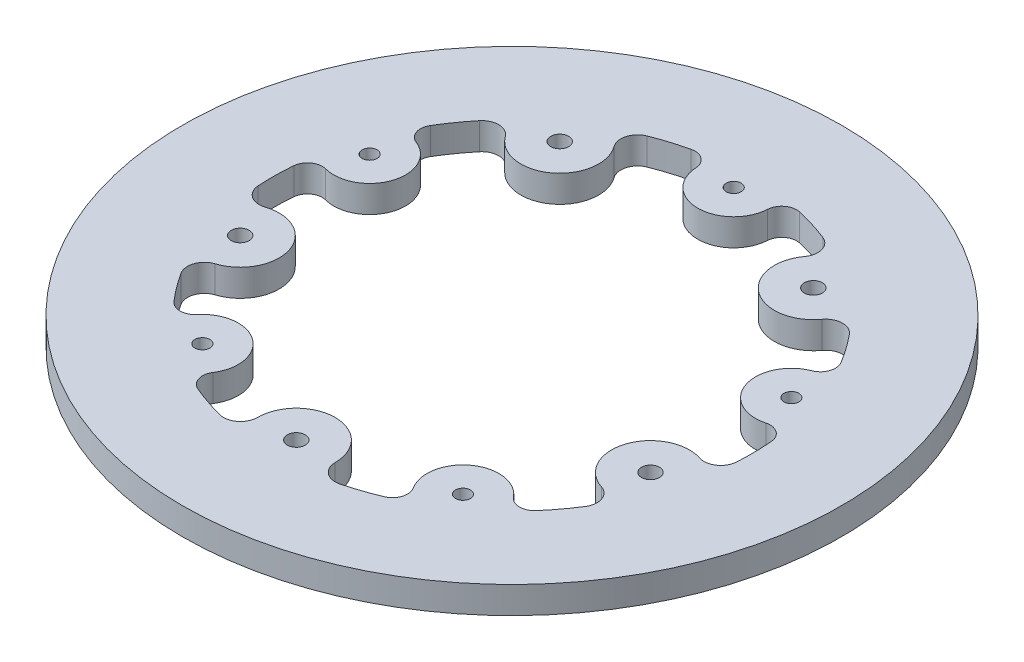
SolidWorks part; units mm, degrees
ref_plane "Front" through (0, 0, 0) normal (0, 0, 1) x (1, 0, 0)
ref_plane "Top" through (0, 0, 0) normal (0, 1, 0) x (1, 0, 0)
ref_plane "Right" through (0, 0, 0) normal (1, 0, 0) x (0, 0, -1)
sketch "Sketch2" plane through (0, 0, 0) normal (0, 1, 0) x (1, 0, 0)
  line L0 (0, 0) -> (0, 110) construction
  line L1 (0, 0) -> (104.6162, 33.9919) construction
  line L2 (0, 0) -> (64.6564, -88.9919) construction
  line L3 (0, 0) -> (-64.6564, -88.9919) construction
  line L4 (0, 0) -> (-104.6162, 33.9919) construction
  line L5 (0, 0) -> (0, -80) construction
  line L6 (-10.8095, -80) -> (10.8095, -80) construction
  line L7 (-12.6491, -75) -> (12.6491, -75) construction
  line L8 (-13, -72) -> (13, -72) construction
  line L9 (-13, -72) -> (-13, -52.7888) construction
  line L10 (0, 0) -> (-76.0845, -24.7214) construction
  line L11 (-75.238, -11.1463) -> (-67.4204, -35.2063) construction
  line L12 (-72.4933, -9.8855) -> (-64.4588, -34.613) construction
  line L14 (0, 0) -> (-47.0228, 64.7214) construction
  line L15 (-33.8505, 68.1112) -> (-54.3172, 53.2413) construction
  line L16 (-31.8033, 65.8904) -> (-52.8378, 50.608) construction
  line L17 (-47.0228, 64.7214) -> (-55.7679, 58.3677) construction
  line L18 (0, 0) -> (47.0228, 64.7214) construction
  line L19 (54.3172, 53.2413) -> (33.8505, 68.1112) construction
  line L20 (52.8378, 50.608) -> (31.8033, 65.8904) construction
  line L21 (55.7679, 58.3677) -> (38.2778, 71.075) construction
  line L22 (0, 0) -> (76.0845, -24.7214) construction
  line L23 (67.4204, -35.2063) -> (75.238, -11.1463) construction
  line L24 (64.4588, -34.613) -> (72.4933, -9.8855) construction
  line L25 (72.7442, -35.0018) -> (79.4248, -14.4409) construction
  line L26 (-79.4248, -14.4409) -> (-76.0845, -24.7214) construction
  arc A0 (-18.1052, 77.9243) -> (-29.3118, 74.4367) centre (0, 0) ccw
  circle A1 centre (0, 0) radius 110
  circle A2 centre (0, 74) radius 6 construction
  circle A3 centre (0, 74) radius 2
  arc A4 (-11.9814, 73.3323) -> (11.9814, 73.3323) centre (0, 74) ccw
  circle A5 centre (70.3782, 22.8673) radius 2
  circle A6 centre (70.3782, 22.8673) radius 6 construction
  arc A7 (66.0407, 34.0559) -> (73.4456, 11.2659) centre (70.3782, 22.8673) ccw
  circle A8 centre (43.4961, -59.8673) radius 2
  circle A9 centre (43.4961, -59.8673) radius 6 construction
  arc A10 (52.7968, -52.2846) -> (33.4105, -66.3696) centre (43.4961, -59.8673) ccw
  circle A11 centre (-43.4961, -59.8673) radius 2
  circle A12 centre (-43.4961, -59.8673) radius 6 construction
  arc A13 (-33.4105, -66.3696) -> (-52.7968, -52.2846) centre (-43.4961, -59.8673) ccw
  circle A14 centre (-70.3782, 22.8673) radius 2
  circle A15 centre (-70.3782, 22.8673) radius 6 construction
  arc A16 (-73.4456, 11.2659) -> (-66.0407, 34.0559) centre (-70.3782, 22.8673) ccw
  arc A17 (68.5156, 41.299) -> (61.7356, 50.8794) centre (0, 0) ccw
  arc A18 (60.4502, -52.4001) -> (67.4665, -42.9915) centre (0, 0) ccw
  arc A19 (-31.1553, -73.6841) -> (-20.039, -77.4496) centre (0, 0) ccw
  arc A20 (-79.7053, 6.8608) -> (-79.8513, -4.875) centre (0, 0) ccw
  circle A21 centre (0, -72) radius 3
  arc A22 (-13, -72) -> (13, -72) centre (0, -72) cw
  arc A23 (-13, -72) -> (-20.039, -77.4496) centre (-18.629, -72) cw
  arc A24 (13, -72) -> (20.039, -77.4496) centre (18.629, -72) ccw
  arc A25 (-72.4933, -9.8855) -> (-79.8513, -4.875) centre (-74.2328, -4.532) cw
  circle A26 centre (-68.4761, -22.2492) radius 3
  arc A27 (-72.4933, -9.8855) -> (-64.4588, -34.613) centre (-68.4761, -22.2492) cw
  arc A28 (-64.4588, -34.613) -> (-67.4665, -42.9915) centre (-62.7194, -39.9665) ccw
  arc A29 (-31.8033, 65.8904) -> (-29.3118, 74.4367) centre (-27.2493, 69.1991) cw
  circle A30 centre (-42.3205, 58.2492) radius 3
  arc A31 (-31.8033, 65.8904) -> (-52.8378, 50.608) centre (-42.3205, 58.2492) cw
  arc A32 (-52.8378, 50.608) -> (-61.7356, 50.8794) centre (-57.3917, 47.2994) ccw
  arc A33 (52.8378, 50.608) -> (61.7356, 50.8794) centre (57.3917, 47.2994) cw
  circle A34 centre (42.3205, 58.2492) radius 3
  arc A35 (52.8378, 50.608) -> (31.8033, 65.8904) centre (42.3205, 58.2492) cw
  arc A36 (31.8033, 65.8904) -> (29.3118, 74.4367) centre (27.2493, 69.1991) ccw
  arc A37 (64.4588, -34.613) -> (67.4665, -42.9915) centre (62.7194, -39.9665) cw
  circle A38 centre (68.4761, -22.2492) radius 3
  arc A39 (64.4588, -34.613) -> (72.4933, -9.8855) centre (68.4761, -22.2492) cw
  arc A40 (72.4933, -9.8855) -> (79.8513, -4.875) centre (74.2328, -4.532) ccw
  arc A41 (20.039, -77.4496) -> (31.1553, -73.6841) centre (0, 0) ccw
  arc A42 (-20.039, -77.4496) -> (20.039, -77.4496) centre (0, 0) ccw construction
  arc A43 (79.8513, -4.875) -> (79.7053, 6.8608) centre (0, 0) ccw
  arc A44 (29.3118, 74.4367) -> (18.1052, 77.9243) centre (0, 0) ccw
  arc A45 (-61.7356, 50.8794) -> (-68.5156, 41.299) centre (0, 0) ccw
  arc A46 (-67.4665, -42.9915) -> (-60.4502, -52.4001) centre (0, 0) ccw
  arc A47 (-66.0407, 34.0559) -> (-68.5156, 41.299) centre (-64.2334, 38.7179) cw
  arc A48 (-73.4456, 11.2659) -> (-79.7053, 6.8608) centre (-74.7237, 6.432) ccw
  arc A49 (-52.7968, -52.2846) -> (-60.4502, -52.4001) centre (-56.6721, -49.1251) cw
  arc A50 (-33.4105, -66.3696) -> (-31.1553, -73.6841) centre (-29.2081, -69.0788) ccw
  arc A51 (52.7968, -52.2846) -> (60.4502, -52.4001) centre (56.6721, -49.1251) ccw
  arc A52 (33.4105, -66.3696) -> (31.1553, -73.6841) centre (29.2081, -69.0788) cw
  arc A53 (73.4456, 11.2659) -> (79.7053, 6.8608) centre (74.7237, 6.432) cw
  arc A54 (66.0407, 34.0559) -> (68.5156, 41.299) centre (64.2334, 38.7179) ccw
  arc A55 (-11.9814, 73.3323) -> (-18.1052, 77.9243) centre (-16.9737, 73.0541) ccw
  arc A56 (11.9814, 73.3323) -> (18.1052, 77.9243) centre (16.9737, 73.0541) cw
  point P36 (0, 0)
  point P38 (0, -80)
  point P39 (0, -80)
  point P44 (0, -75)
  point P51 (0, -72)
  point P111 (0, 0)
  dimension "D1" = 160
  dimension "D2" = 30
  dimension "D3" = 12
  dimension "D4" = 4
  dimension "D5" = 6
  dimension "D6" = 5
  dimension "D7" = 6
  dimension "D9" = 10
  dimension "D11" = 5
  dimension "D8" = 5
  dimension "D10" = 5
extrude "Boss-Extrude1" add sketch "Sketch2" along normal blind 9
sketch "Sketch3" [suppressed] plane through (0, 9, 0) normal (0, 1, 0) x (1, 0, 0)
  line L0 (0, 0) -> (0, 116.2564) construction
  line L1 (4.9616, 114.4288) -> (5.0361, 116.1472) construction
  line L2 (0, 114.5364) -> (0, 115.3964) construction
  line L3 (4.9616, 114.4288) -> (4.9988, 115.288) construction
  circle A0 centre (0, 0) radius 116.2564 construction
  circle A1 centre (0, 0) radius 112.4564 construction
  circle A2 centre (0, 0) radius 114.5364 construction
  arc A3 (-2.0799, 114.5175) -> (2.0799, 114.5175) centre (0, 114.5364) ccw
  arc A4 (2.8828, 114.5001) -> (7.0387, 114.3199) centre (4.9616, 114.4288) ccw
  arc A5 (7.8401, 114.2677) -> (11.9843, 113.9077) centre (9.9138, 114.1065) ccw
  arc A6 (12.7827, 113.8208) -> (16.9074, 113.2816) centre (14.8475, 113.5699) ccw
  arc A7 (17.7012, 113.1603) -> (21.7987, 112.4428) centre (19.7532, 112.8202) ccw
  arc A8 (22.5866, 112.2872) -> (26.6492, 111.393) centre (24.6219, 111.8586) ccw
  arc A9 (27.4295, 111.2034) -> (31.4495, 110.134) centre (29.4444, 110.687) ccw
  arc A10 (32.221, 109.9108) -> (36.1909, 108.6683) centre (34.2116, 109.3076) ccw
  arc A11 (36.9519, 108.4119) -> (40.8643, 106.9985) centre (38.9145, 107.723) ccw
  arc A12 (41.6135, 106.7094) -> (45.461, 105.1279) centre (43.5444, 105.9361) ccw
  arc A13 (46.197, 104.8066) -> (49.9723, 103.0599) centre (48.0926, 103.9504) ccw
  arc A14 (50.6937, 102.707) -> (54.3898, 100.7984) centre (52.5504, 101.7695) ccw
  arc A15 (55.0952, 100.4146) -> (58.7052, 98.3477) centre (56.9096, 99.3975) ccw
  arc A16 (59.3934, 97.9337) -> (62.9104, 95.7124) centre (61.162, 96.839) ccw
  arc A17 (63.58, 95.2689) -> (66.9975, 92.8973) centre (65.2995, 94.0986) ccw
  arc A18 (67.6472, 92.4253) -> (70.9588, 89.9079) centre (69.3145, 91.1816) ccw
  arc A19 (71.5875, 89.4081) -> (74.7869, 86.7496) centre (73.1993, 88.0934) ccw
  arc A20 (75.3933, 86.2231) -> (78.4746, 83.4285) centre (76.9466, 84.8398) ccw
  arc A21 (79.0576, 82.8762) -> (82.015, 79.9508) centre (80.5496, 81.4269) ccw
  arc A22 (82.5735, 79.3738) -> (85.4013, 76.3229) centre (84.0013, 77.8612) ccw
  arc A23 (85.9344, 75.7223) -> (88.6274, 72.5518) centre (87.2953, 74.1493) ccw
  arc A24 (89.1339, 71.9286) -> (91.687, 68.6445) centre (90.4254, 70.2981) ccw
  arc A25 (92.1661, 67.9999) -> (94.5746, 64.6083) centre (93.3857, 66.315) ccw
  arc A26 (95.0252, 63.9436) -> (97.2845, 60.4508) centre (96.1707, 62.2074) ccw
  arc A27 (97.706, 59.7672) -> (99.8119, 56.1798) centre (98.7752, 57.983) ccw
  arc A28 (100.2033, 55.4786) -> (102.1518, 51.8033) centre (101.1943, 53.6498) ccw
  arc A29 (102.5125, 51.0858) -> (104.3, 47.3296) centre (103.4233, 49.2158) ccw
  arc A30 (104.6293, 46.5972) -> (106.2523, 42.767) centre (105.4582, 44.6895) ccw
  arc A31 (106.5496, 42.021) -> (108.0052, 38.1242) centre (107.2951, 40.0792) ccw
  arc A32 (108.2699, 37.366) -> (109.5553, 33.4097) centre (108.9306, 35.3937) ccw
  arc A33 (109.7869, 32.6408) -> (110.8997, 28.6326) centre (110.3615, 30.6417) ccw
  arc A34 (111.0978, 27.8543) -> (112.036, 23.8017) centre (111.5853, 25.8322) ccw
  arc A35 (112.2001, 23.0155) -> (112.9619, 18.9261) centre (112.5996, 20.9743) ccw
  arc A36 (113.0918, 18.1336) -> (113.6757, 14.0149) centre (113.4024, 16.0769) ccw
  arc A37 (113.7712, 13.2175) -> (114.1761, 9.0775) centre (113.9924, 11.1493) ccw
  arc A38 (114.2369, 8.2767) -> (114.4621, 4.123) centre (114.3684, 6.2009) ccw
  arc A39 (114.4882, 3.3203) -> (114.5333, -0.8392) centre (114.5296, 1.2408) ccw
  arc A40 (114.5246, -1.6423) -> (114.3894, -5.7999) centre (114.4759, -3.7217) ccw
  arc A41 (114.3459, -6.6018) -> (114.0308, -10.7497) centre (114.2072, -8.6771) ccw
  arc A42 (113.9526, -11.5489) -> (113.4581, -15.6792) centre (113.7241, -13.6163) ccw
  arc A43 (113.3454, -16.4744) -> (112.6724, -20.5794) centre (113.0275, -18.5299) ccw
  arc A44 (112.5253, -21.3689) -> (111.6752, -25.4409) centre (112.1187, -23.4087) ccw
  arc A45 (111.494, -26.2233) -> (110.4683, -30.2546) centre (110.9994, -28.2436) ccw
  arc A46 (110.2534, -31.0284) -> (109.054, -35.0116) centre (109.6718, -33.0255) ccw
  arc A47 (108.8058, -35.7753) -> (107.4349, -39.7028) centre (108.1382, -37.7453) ccw
  arc A48 (107.1539, -40.4551) -> (105.6142, -44.3195) centre (106.4016, -42.3943) ccw
  arc A49 (105.3009, -45.0589) -> (103.5952, -48.853) centre (104.4653, -46.9637) ccw
  arc A50 (103.2501, -49.5781) -> (101.3817, -53.2947) centre (102.3328, -51.4449) ccw
  arc A51 (101.0056, -54.0042) -> (98.9779, -57.6364) centre (100.0082, -55.8295) ccw
  arc A52 (98.5713, -58.329) -> (96.3882, -61.8699) centre (97.4959, -60.1093) ccw
  arc A53 (95.9521, -62.5442) -> (93.6176, -65.9872) centre (94.8005, -64.2763) ccw
  arc A54 (93.1527, -66.642) -> (90.6713, -69.9807) centre (91.9271, -68.3226) ccw
  arc A55 (90.1784, -70.6147) -> (87.5547, -73.8428) centre (88.8812, -72.2407) ccw
  arc A56 (87.0348, -74.4548) -> (84.2737, -77.5662) centre (85.6684, -76.0231) ccw
  arc A57 (83.7278, -78.1552) -> (80.8345, -81.144) centre (82.2947, -79.6628) ccw
  arc A58 (80.2636, -81.7088) -> (77.2436, -84.5695) centre (78.7666, -83.1529) ccw
  arc A59 (76.6487, -85.109) -> (73.5076, -87.8362) centre (75.0906, -86.4869) ccw
  arc A60 (72.89, -88.3495) -> (69.6337, -90.938) centre (71.2736, -89.6585) ccw
  arc A61 (68.9944, -91.424) -> (65.629, -93.8691) centre (67.3228, -92.6619) ccw
  arc A62 (64.9692, -94.327) -> (61.5011, -96.624) centre (63.2456, -95.4912) ccw
  arc A63 (60.8221, -97.0528) -> (57.2577, -99.1974) centre (59.0497, -98.1413) ccw
  arc A64 (56.5608, -99.5964) -> (52.9069, -101.5846) centre (54.7429, -100.6071) ccw
  arc A65 (52.1933, -101.9531) -> (48.4567, -103.7811) centre (50.3333, -102.8841) ccw
  arc A66 (47.7279, -104.1183) -> (43.9155, -105.7828) centre (45.8293, -104.9679) ccw
  arc A67 (43.1728, -106.0881) -> (39.2919, -107.5859) centre (41.2392, -106.8546) ccw
  arc A68 (38.5366, -107.8587) -> (34.5946, -109.187) centre (36.5716, -108.5407) ccw
  arc A69 (33.8282, -109.4268) -> (29.8323, -110.5831) centre (31.8355, -110.0231) ccw
  arc A70 (29.0562, -110.7895) -> (25.0139, -111.7716) centre (27.0395, -111.2989) ccw
  arc A71 (24.2296, -111.9442) -> (20.1486, -112.7502) centre (22.1928, -112.3657) ccw
  arc A72 (19.3576, -112.8887) -> (15.2455, -113.5172) centre (17.3044, -113.2216) ccw
  arc A73 (14.4492, -113.6213) -> (10.3138, -114.071) centre (12.3836, -113.8649) ccw
  arc A74 (9.5137, -114.1406) -> (5.3627, -114.4107) centre (7.4394, -114.2945) ccw
  arc A75 (4.5604, -114.4455) -> (0.4015, -114.5357) centre (2.4814, -114.5095) ccw
  arc A76 (-0.4015, -114.5357) -> (-4.5604, -114.4455) centre (-2.4814, -114.5095) ccw
  arc A77 (-5.3627, -114.4107) -> (-9.5137, -114.1406) centre (-7.4394, -114.2945) ccw
  arc A78 (-10.3138, -114.071) -> (-14.4492, -113.6213) centre (-12.3836, -113.8649) ccw
  arc A79 (-15.2455, -113.5172) -> (-19.3576, -112.8887) centre (-17.3044, -113.2216) ccw
  arc A80 (-20.1486, -112.7502) -> (-24.2296, -111.9442) centre (-22.1928, -112.3657) ccw
  arc A81 (-25.0139, -111.7716) -> (-29.0562, -110.7895) centre (-27.0395, -111.2989) ccw
  arc A82 (-29.8323, -110.5831) -> (-33.8282, -109.4268) centre (-31.8355, -110.0231) ccw
  arc A83 (-34.5946, -109.187) -> (-38.5366, -107.8587) centre (-36.5716, -108.5407) ccw
  arc A84 (-39.2919, -107.5859) -> (-43.1728, -106.0881) centre (-41.2392, -106.8546) ccw
  arc A85 (-43.9155, -105.7828) -> (-47.7279, -104.1183) centre (-45.8293, -104.9679) ccw
  arc A86 (-48.4567, -103.7811) -> (-52.1933, -101.9531) centre (-50.3333, -102.8841) ccw
  arc A87 (-52.9069, -101.5846) -> (-56.5608, -99.5964) centre (-54.7429, -100.6071) ccw
  arc A88 (-57.2577, -99.1974) -> (-60.8221, -97.0528) centre (-59.0497, -98.1413) ccw
  arc A89 (-61.5011, -96.624) -> (-64.9692, -94.327) centre (-63.2456, -95.4912) ccw
  arc A90 (-65.629, -93.8691) -> (-68.9944, -91.424) centre (-67.3228, -92.6619) ccw
  arc A91 (-69.6337, -90.938) -> (-72.89, -88.3495) centre (-71.2736, -89.6585) ccw
  arc A92 (-73.5076, -87.8362) -> (-76.6487, -85.109) centre (-75.0906, -86.4869) ccw
  arc A93 (-77.2436, -84.5695) -> (-80.2636, -81.7088) centre (-78.7666, -83.1529) ccw
  arc A94 (-80.8345, -81.144) -> (-83.7278, -78.1552) centre (-82.2947, -79.6628) ccw
  arc A95 (-84.2737, -77.5662) -> (-87.0348, -74.4548) centre (-85.6684, -76.0231) ccw
  arc A96 (-87.5547, -73.8428) -> (-90.1784, -70.6147) centre (-88.8812, -72.2407) ccw
  arc A97 (-90.6713, -69.9807) -> (-93.1527, -66.642) centre (-91.9271, -68.3226) ccw
  arc A98 (-93.6176, -65.9872) -> (-95.9521, -62.5442) centre (-94.8005, -64.2763) ccw
  arc A99 (-96.3882, -61.8699) -> (-98.5713, -58.329) centre (-97.4959, -60.1093) ccw
  arc A100 (-98.9779, -57.6364) -> (-101.0056, -54.0042) centre (-100.0082, -55.8295) ccw
  arc A101 (-101.3817, -53.2947) -> (-103.2501, -49.5781) centre (-102.3328, -51.4449) ccw
  arc A102 (-103.5952, -48.853) -> (-105.3009, -45.0589) centre (-104.4653, -46.9637) ccw
  arc A103 (-105.6142, -44.3195) -> (-107.1539, -40.4551) centre (-106.4016, -42.3943) ccw
  arc A104 (-107.4349, -39.7028) -> (-108.8058, -35.7753) centre (-108.1382, -37.7453) ccw
  arc A105 (-109.054, -35.0116) -> (-110.2534, -31.0284) centre (-109.6718, -33.0255) ccw
  arc A106 (-110.4683, -30.2546) -> (-111.494, -26.2233) centre (-110.9994, -28.2436) ccw
  arc A107 (-111.6752, -25.4409) -> (-112.5253, -21.3689) centre (-112.1187, -23.4087) ccw
  arc A108 (-112.6724, -20.5794) -> (-113.3454, -16.4744) centre (-113.0275, -18.5299) ccw
  arc A109 (-113.4581, -15.6792) -> (-113.9526, -11.5489) centre (-113.7241, -13.6163) ccw
  arc A110 (-114.0308, -10.7497) -> (-114.3459, -6.6018) centre (-114.2072, -8.6771) ccw
  arc A111 (-114.3894, -5.7999) -> (-114.5246, -1.6423) centre (-114.4759, -3.7217) ccw
  arc A112 (-114.5333, -0.8392) -> (-114.4882, 3.3203) centre (-114.5296, 1.2408) ccw
  arc A113 (-114.4621, 4.123) -> (-114.2369, 8.2767) centre (-114.3684, 6.2009) ccw
  arc A114 (-114.1761, 9.0775) -> (-113.7712, 13.2175) centre (-113.9924, 11.1493) ccw
  arc A115 (-113.6757, 14.0149) -> (-113.0918, 18.1336) centre (-113.4024, 16.0769) ccw
  arc A116 (-112.9619, 18.9261) -> (-112.2001, 23.0155) centre (-112.5996, 20.9743) ccw
  arc A117 (-112.036, 23.8017) -> (-111.0978, 27.8543) centre (-111.5853, 25.8322) ccw
  arc A118 (-110.8997, 28.6326) -> (-109.7869, 32.6408) centre (-110.3615, 30.6417) ccw
  arc A119 (-109.5553, 33.4097) -> (-108.2699, 37.366) centre (-108.9306, 35.3937) ccw
  arc A120 (-108.0052, 38.1242) -> (-106.5496, 42.021) centre (-107.2951, 40.0792) ccw
  arc A121 (-106.2523, 42.767) -> (-104.6293, 46.5972) centre (-105.4582, 44.6895) ccw
  arc A122 (-104.3, 47.3296) -> (-102.5125, 51.0858) centre (-103.4233, 49.2158) ccw
  arc A123 (-102.1518, 51.8033) -> (-100.2033, 55.4786) centre (-101.1943, 53.6498) ccw
  arc A124 (-99.8119, 56.1798) -> (-97.706, 59.7672) centre (-98.7752, 57.983) ccw
  arc A125 (-97.2845, 60.4508) -> (-95.0252, 63.9436) centre (-96.1707, 62.2074) ccw
  arc A126 (-94.5746, 64.6083) -> (-92.1661, 67.9999) centre (-93.3857, 66.315) ccw
  arc A127 (-91.687, 68.6445) -> (-89.1339, 71.9286) centre (-90.4254, 70.2981) ccw
  arc A128 (-88.6274, 72.5518) -> (-85.9344, 75.7223) centre (-87.2953, 74.1493) ccw
  arc A129 (-85.4013, 76.3229) -> (-82.5735, 79.3738) centre (-84.0013, 77.8612) ccw
  arc A130 (-82.015, 79.9508) -> (-79.0576, 82.8762) centre (-80.5496, 81.4269) ccw
  arc A131 (-78.4746, 83.4285) -> (-75.3933, 86.2231) centre (-76.9466, 84.8398) ccw
  arc A132 (-74.7869, 86.7496) -> (-71.5875, 89.4081) centre (-73.1993, 88.0934) ccw
  arc A133 (-70.9588, 89.9079) -> (-67.6472, 92.4253) centre (-69.3145, 91.1816) ccw
  arc A134 (-66.9975, 92.8973) -> (-63.58, 95.2689) centre (-65.2995, 94.0986) ccw
  arc A135 (-62.9104, 95.7124) -> (-59.3934, 97.9337) centre (-61.162, 96.839) ccw
  arc A136 (-58.7052, 98.3477) -> (-55.0952, 100.4146) centre (-56.9096, 99.3975) ccw
  arc A137 (-54.3898, 100.7984) -> (-50.6937, 102.707) centre (-52.5504, 101.7695) ccw
  arc A138 (-49.9723, 103.0599) -> (-46.197, 104.8066) centre (-48.0926, 103.9504) ccw
  arc A139 (-45.461, 105.1279) -> (-41.6135, 106.7094) centre (-43.5444, 105.9361) ccw
  arc A140 (-40.8643, 106.9985) -> (-36.9519, 108.4119) centre (-38.9145, 107.723) ccw
  arc A141 (-36.1909, 108.6683) -> (-32.221, 109.9108) centre (-34.2116, 109.3076) ccw
  arc A142 (-31.4495, 110.134) -> (-27.4295, 111.2034) centre (-29.4444, 110.687) ccw
  arc A143 (-26.6492, 111.393) -> (-22.5866, 112.2872) centre (-24.6219, 111.8586) ccw
  arc A144 (-21.7987, 112.4428) -> (-17.7012, 113.1603) centre (-19.7532, 112.8202) ccw
  arc A145 (-16.9074, 113.2816) -> (-12.7827, 113.8208) centre (-14.8475, 113.5699) ccw
  arc A146 (-11.9843, 113.9077) -> (-7.8401, 114.2677) centre (-9.9138, 114.1065) ccw
  arc A147 (-7.0387, 114.3199) -> (-2.8828, 114.5001) centre (-4.9616, 114.4288) ccw
  arc A148 (2.0799, 114.5175) -> (2.8828, 114.5001) centre (0, 0) cw
  arc A149 (7.0387, 114.3199) -> (7.8401, 114.2677) centre (0, 0) cw
  arc A150 (11.9843, 113.9077) -> (12.7827, 113.8208) centre (0, 0) cw
  arc A151 (16.9074, 113.2816) -> (17.7012, 113.1603) centre (0, 0) cw
  arc A152 (21.7987, 112.4428) -> (22.5866, 112.2872) centre (0, 0) cw
  arc A153 (26.6492, 111.393) -> (27.4295, 111.2034) centre (0, 0) cw
  arc A154 (31.4495, 110.134) -> (32.221, 109.9108) centre (0, 0) cw
  arc A155 (36.1909, 108.6683) -> (36.9519, 108.4119) centre (0, 0) cw
  arc A156 (40.8643, 106.9985) -> (41.6135, 106.7094) centre (0, 0) cw
  arc A157 (45.461, 105.1279) -> (46.197, 104.8066) centre (0, 0) cw
  arc A158 (49.9723, 103.0599) -> (50.6937, 102.707) centre (0, 0) cw
  arc A159 (54.3898, 100.7984) -> (55.0952, 100.4146) centre (0, 0) cw
  arc A160 (58.7052, 98.3477) -> (59.3934, 97.9337) centre (0, 0) cw
  arc A161 (62.9104, 95.7124) -> (63.58, 95.2689) centre (0, 0) cw
  arc A162 (66.9975, 92.8973) -> (67.6472, 92.4253) centre (0, 0) cw
  arc A163 (70.9588, 89.9079) -> (71.5875, 89.4081) centre (0, 0) cw
  arc A164 (74.7869, 86.7496) -> (75.3933, 86.2231) centre (0, 0) cw
  arc A165 (78.4746, 83.4285) -> (79.0576, 82.8762) centre (0, 0) cw
  arc A166 (82.015, 79.9508) -> (82.5735, 79.3738) centre (0, 0) cw
  arc A167 (85.4013, 76.3229) -> (85.9344, 75.7223) centre (0, 0) cw
  arc A168 (88.6274, 72.5518) -> (89.1339, 71.9286) centre (0, 0) cw
  arc A169 (91.687, 68.6445) -> (92.1661, 67.9999) centre (0, 0) cw
  arc A170 (94.5746, 64.6083) -> (95.0252, 63.9436) centre (0, 0) cw
  arc A171 (97.2845, 60.4508) -> (97.706, 59.7672) centre (0, 0) cw
  arc A172 (99.8119, 56.1798) -> (100.2033, 55.4786) centre (0, 0) cw
  arc A173 (102.1518, 51.8033) -> (102.5125, 51.0858) centre (0, 0) cw
  arc A174 (104.3, 47.3296) -> (104.6293, 46.5972) centre (0, 0) cw
  arc A175 (106.2523, 42.767) -> (106.5496, 42.021) centre (0, 0) cw
  arc A176 (108.0052, 38.1242) -> (108.2699, 37.366) centre (0, 0) cw
  arc A177 (109.5553, 33.4097) -> (109.7869, 32.6408) centre (0, 0) cw
  arc A178 (110.8997, 28.6326) -> (111.0978, 27.8543) centre (0, 0) cw
  arc A179 (112.036, 23.8017) -> (112.2001, 23.0155) centre (0, 0) cw
  arc A180 (112.9619, 18.9261) -> (113.0918, 18.1336) centre (0, 0) cw
  arc A181 (113.6757, 14.0149) -> (113.7712, 13.2175) centre (0, 0) cw
  arc A182 (114.1761, 9.0775) -> (114.2369, 8.2767) centre (0, 0) cw
  arc A183 (114.4621, 4.123) -> (114.4882, 3.3203) centre (0, 0) cw
  arc A184 (114.5333, -0.8392) -> (114.5246, -1.6423) centre (0, 0) cw
  arc A185 (114.3894, -5.7999) -> (114.3459, -6.6018) centre (0, 0) cw
  arc A186 (114.0308, -10.7497) -> (113.9526, -11.5489) centre (0, 0) cw
  arc A187 (113.4581, -15.6792) -> (113.3454, -16.4744) centre (0, 0) cw
  arc A188 (112.6724, -20.5794) -> (112.5253, -21.3689) centre (0, 0) cw
  arc A189 (111.6752, -25.4409) -> (111.494, -26.2233) centre (0, 0) cw
  arc A190 (110.4683, -30.2546) -> (110.2534, -31.0284) centre (0, 0) cw
  arc A191 (109.054, -35.0116) -> (108.8058, -35.7753) centre (0, 0) cw
  arc A192 (107.4349, -39.7028) -> (107.1539, -40.4551) centre (0, 0) cw
  arc A193 (105.6142, -44.3195) -> (105.3009, -45.0589) centre (0, 0) cw
  arc A194 (103.5952, -48.853) -> (103.2501, -49.5781) centre (0, 0) cw
  arc A195 (101.3817, -53.2947) -> (101.0056, -54.0042) centre (0, 0) cw
  arc A196 (98.9779, -57.6364) -> (98.5713, -58.329) centre (0, 0) cw
  arc A197 (96.3882, -61.8699) -> (95.9521, -62.5442) centre (0, 0) cw
  arc A198 (93.6176, -65.9872) -> (93.1527, -66.642) centre (0, 0) cw
  arc A199 (90.6713, -69.9807) -> (90.1784, -70.6147) centre (0, 0) cw
  arc A200 (87.5547, -73.8428) -> (87.0348, -74.4548) centre (0, 0) cw
  arc A201 (84.2737, -77.5662) -> (83.7278, -78.1552) centre (0, 0) cw
  arc A202 (80.8345, -81.144) -> (80.2636, -81.7088) centre (0, 0) cw
  arc A203 (77.2436, -84.5695) -> (76.6487, -85.109) centre (0, 0) cw
  arc A204 (73.5076, -87.8362) -> (72.89, -88.3495) centre (0, 0) cw
  arc A205 (69.6337, -90.938) -> (68.9944, -91.424) centre (0, 0) cw
  arc A206 (65.629, -93.8691) -> (64.9692, -94.327) centre (0, 0) cw
  arc A207 (61.5011, -96.624) -> (60.8221, -97.0528) centre (0, 0) cw
  arc A208 (57.2577, -99.1974) -> (56.5608, -99.5964) centre (0, 0) cw
  arc A209 (52.9069, -101.5846) -> (52.1933, -101.9531) centre (0, 0) cw
  arc A210 (48.4567, -103.7811) -> (47.7279, -104.1183) centre (0, 0) cw
  arc A211 (43.9155, -105.7828) -> (43.1728, -106.0881) centre (0, 0) cw
  arc A212 (39.2919, -107.5859) -> (38.5366, -107.8587) centre (0, 0) cw
  arc A213 (34.5946, -109.187) -> (33.8282, -109.4268) centre (0, 0) cw
  arc A214 (29.8323, -110.5831) -> (29.0562, -110.7895) centre (0, 0) cw
  arc A215 (25.0139, -111.7716) -> (24.2296, -111.9442) centre (0, 0) cw
  arc A216 (20.1486, -112.7502) -> (19.3576, -112.8887) centre (0, 0) cw
  arc A217 (15.2455, -113.5172) -> (14.4492, -113.6213) centre (0, 0) cw
  arc A218 (10.3138, -114.071) -> (9.5137, -114.1406) centre (0, 0) cw
  arc A219 (5.3627, -114.4107) -> (4.5604, -114.4455) centre (0, 0) cw
  arc A220 (0.4015, -114.5357) -> (-0.4015, -114.5357) centre (0, 0) cw
  arc A221 (-4.5604, -114.4455) -> (-5.3627, -114.4107) centre (0, 0) cw
  arc A222 (-9.5137, -114.1406) -> (-10.3138, -114.071) centre (0, 0) cw
  arc A223 (-14.4492, -113.6213) -> (-15.2455, -113.5172) centre (0, 0) cw
  arc A224 (-19.3576, -112.8887) -> (-20.1486, -112.7502) centre (0, 0) cw
  arc A225 (-24.2296, -111.9442) -> (-25.0139, -111.7716) centre (0, 0) cw
  arc A226 (-29.0562, -110.7895) -> (-29.8323, -110.5831) centre (0, 0) cw
  arc A227 (-33.8282, -109.4268) -> (-34.5946, -109.187) centre (0, 0) cw
  arc A228 (-38.5366, -107.8587) -> (-39.2919, -107.5859) centre (0, 0) cw
  arc A229 (-43.1728, -106.0881) -> (-43.9155, -105.7828) centre (0, 0) cw
  arc A230 (-47.7279, -104.1183) -> (-48.4567, -103.7811) centre (0, 0) cw
  arc A231 (-52.1933, -101.9531) -> (-52.9069, -101.5846) centre (0, 0) cw
  arc A232 (-56.5608, -99.5964) -> (-57.2577, -99.1974) centre (0, 0) cw
  arc A233 (-60.8221, -97.0528) -> (-61.5011, -96.624) centre (0, 0) cw
  arc A234 (-64.9692, -94.327) -> (-65.629, -93.8691) centre (0, 0) cw
  arc A235 (-68.9944, -91.424) -> (-69.6337, -90.938) centre (0, 0) cw
  arc A236 (-72.89, -88.3495) -> (-73.5076, -87.8362) centre (0, 0) cw
  arc A237 (-76.6487, -85.109) -> (-77.2436, -84.5695) centre (0, 0) cw
  arc A238 (-80.2636, -81.7088) -> (-80.8345, -81.144) centre (0, 0) cw
  arc A239 (-83.7278, -78.1552) -> (-84.2737, -77.5662) centre (0, 0) cw
  arc A240 (-87.0348, -74.4548) -> (-87.5547, -73.8428) centre (0, 0) cw
  arc A241 (-90.1784, -70.6147) -> (-90.6713, -69.9807) centre (0, 0) cw
  arc A242 (-93.1527, -66.642) -> (-93.6176, -65.9872) centre (0, 0) cw
  arc A243 (-95.9521, -62.5442) -> (-96.3882, -61.8699) centre (0, 0) cw
  arc A244 (-98.5713, -58.329) -> (-98.9779, -57.6364) centre (0, 0) cw
  arc A245 (-101.0056, -54.0042) -> (-101.3817, -53.2947) centre (0, 0) cw
  arc A246 (-103.2501, -49.5781) -> (-103.5952, -48.853) centre (0, 0) cw
  arc A247 (-105.3009, -45.0589) -> (-105.6142, -44.3195) centre (0, 0) cw
  arc A248 (-107.1539, -40.4551) -> (-107.4349, -39.7028) centre (0, 0) cw
  arc A249 (-108.8058, -35.7753) -> (-109.054, -35.0116) centre (0, 0) cw
  arc A250 (-110.2534, -31.0284) -> (-110.4683, -30.2546) centre (0, 0) cw
  arc A251 (-111.494, -26.2233) -> (-111.6752, -25.4409) centre (0, 0) cw
  arc A252 (-112.5253, -21.3689) -> (-112.6724, -20.5794) centre (0, 0) cw
  arc A253 (-113.3454, -16.4744) -> (-113.4581, -15.6792) centre (0, 0) cw
  arc A254 (-113.9526, -11.5489) -> (-114.0308, -10.7497) centre (0, 0) cw
  arc A255 (-114.3459, -6.6018) -> (-114.3894, -5.7999) centre (0, 0) cw
  arc A256 (-114.5246, -1.6423) -> (-114.5333, -0.8392) centre (0, 0) cw
  arc A257 (-114.4882, 3.3203) -> (-114.4621, 4.123) centre (0, 0) cw
  arc A258 (-114.2369, 8.2767) -> (-114.1761, 9.0775) centre (0, 0) cw
  arc A259 (-113.7712, 13.2175) -> (-113.6757, 14.0149) centre (0, 0) cw
  arc A260 (-113.0918, 18.1336) -> (-112.9619, 18.9261) centre (0, 0) cw
  arc A261 (-112.2001, 23.0155) -> (-112.036, 23.8017) centre (0, 0) cw
  arc A262 (-111.0978, 27.8543) -> (-110.8997, 28.6326) centre (0, 0) cw
  arc A263 (-109.7869, 32.6408) -> (-109.5553, 33.4097) centre (0, 0) cw
  arc A264 (-108.2699, 37.366) -> (-108.0052, 38.1242) centre (0, 0) cw
  arc A265 (-106.5496, 42.021) -> (-106.2523, 42.767) centre (0, 0) cw
  arc A266 (-104.6293, 46.5972) -> (-104.3, 47.3296) centre (0, 0) cw
  arc A267 (-102.5125, 51.0858) -> (-102.1518, 51.8033) centre (0, 0) cw
  arc A268 (-100.2033, 55.4786) -> (-99.8119, 56.1798) centre (0, 0) cw
  arc A269 (-97.706, 59.7672) -> (-97.2845, 60.4508) centre (0, 0) cw
  arc A270 (-95.0252, 63.9436) -> (-94.5746, 64.6083) centre (0, 0) cw
  arc A271 (-92.1661, 67.9999) -> (-91.687, 68.6445) centre (0, 0) cw
  arc A272 (-89.1339, 71.9286) -> (-88.6274, 72.5518) centre (0, 0) cw
  arc A273 (-85.9344, 75.7223) -> (-85.4013, 76.3229) centre (0, 0) cw
  arc A274 (-82.5735, 79.3738) -> (-82.015, 79.9508) centre (0, 0) cw
  arc A275 (-79.0576, 82.8762) -> (-78.4746, 83.4285) centre (0, 0) cw
  arc A276 (-75.3933, 86.2231) -> (-74.7869, 86.7496) centre (0, 0) cw
  arc A277 (-71.5875, 89.4081) -> (-70.9588, 89.9079) centre (0, 0) cw
  arc A278 (-67.6472, 92.4253) -> (-66.9975, 92.8973) centre (0, 0) cw
  arc A279 (-63.58, 95.2689) -> (-62.9104, 95.7124) centre (0, 0) cw
  arc A280 (-59.3934, 97.9337) -> (-58.7052, 98.3477) centre (0, 0) cw
  arc A281 (-55.0952, 100.4146) -> (-54.3898, 100.7984) centre (0, 0) cw
  arc A282 (-50.6937, 102.707) -> (-49.9723, 103.0599) centre (0, 0) cw
  arc A283 (-46.197, 104.8066) -> (-45.461, 105.1279) centre (0, 0) cw
  arc A284 (-41.6135, 106.7094) -> (-40.8643, 106.9985) centre (0, 0) cw
  arc A285 (-36.9519, 108.4119) -> (-36.1909, 108.6683) centre (0, 0) cw
  arc A286 (-32.221, 109.9108) -> (-31.4495, 110.134) centre (0, 0) cw
  arc A287 (-27.4295, 111.2034) -> (-26.6492, 111.393) centre (0, 0) cw
  arc A288 (-22.5866, 112.2872) -> (-21.7987, 112.4428) centre (0, 0) cw
  arc A289 (-17.7012, 113.1603) -> (-16.9074, 113.2816) centre (0, 0) cw
  arc A290 (-12.7827, 113.8208) -> (-11.9843, 113.9077) centre (0, 0) cw
  arc A291 (-7.8401, 114.2677) -> (-7.0387, 114.3199) centre (0, 0) cw
  arc A292 (-2.8828, 114.5001) -> (-2.0799, 114.5175) centre (0, 0) cw
  circle A293 centre (0, 0) radius 110
  circle A294 centre (0, 0) radius 110 construction
  circle A295 centre (0, 0) radius 115.3964 construction
  point P13 (2.0799, 114.5175)
  point P310 (0, 0)
  point P312 (4.9988, 115.288)
  point P734 (0, 0)
  dimension "D1" = 3.8
  dimension "D2" = 2.08
  dimension "D3" = 145
  dimension "D4" = 5
  dimension "D5" = 145
extrude "Boss-Extrude2" [suppressed] add sketch "Sketch3" against normal up to surface (9 mm away)
sketch "Sketch4" plane through (0, 9, 0) normal (0, 1, 0) x (1, 0, 0)
  line L0 (0, 74) -> (0, 0) construction
  line L1 (70.3782, 22.8673) -> (0, 0) construction
  line L2 (43.4961, -59.8673) -> (0, 0) construction
  line L3 (-43.4961, -59.8673) -> (0, 0) construction
  line L4 (-70.3782, 22.8673) -> (0, 0) construction
  circle A0 centre (0, 74) radius 2.5
  circle A1 centre (0, 74) radius 2 construction
  circle A2 centre (70.3782, 22.8673) radius 2.5
  circle A3 centre (43.4961, -59.8673) radius 2.5
  circle A4 centre (-43.4961, -59.8673) radius 2.5
  circle A5 centre (-70.3782, 22.8673) radius 2.5
  point P18 (0, 0)
  dimension "D1" = 5
  dimension "D2" = 5
extrude "Cut-Extrude1" cut sketch "Sketch4" against normal through all
